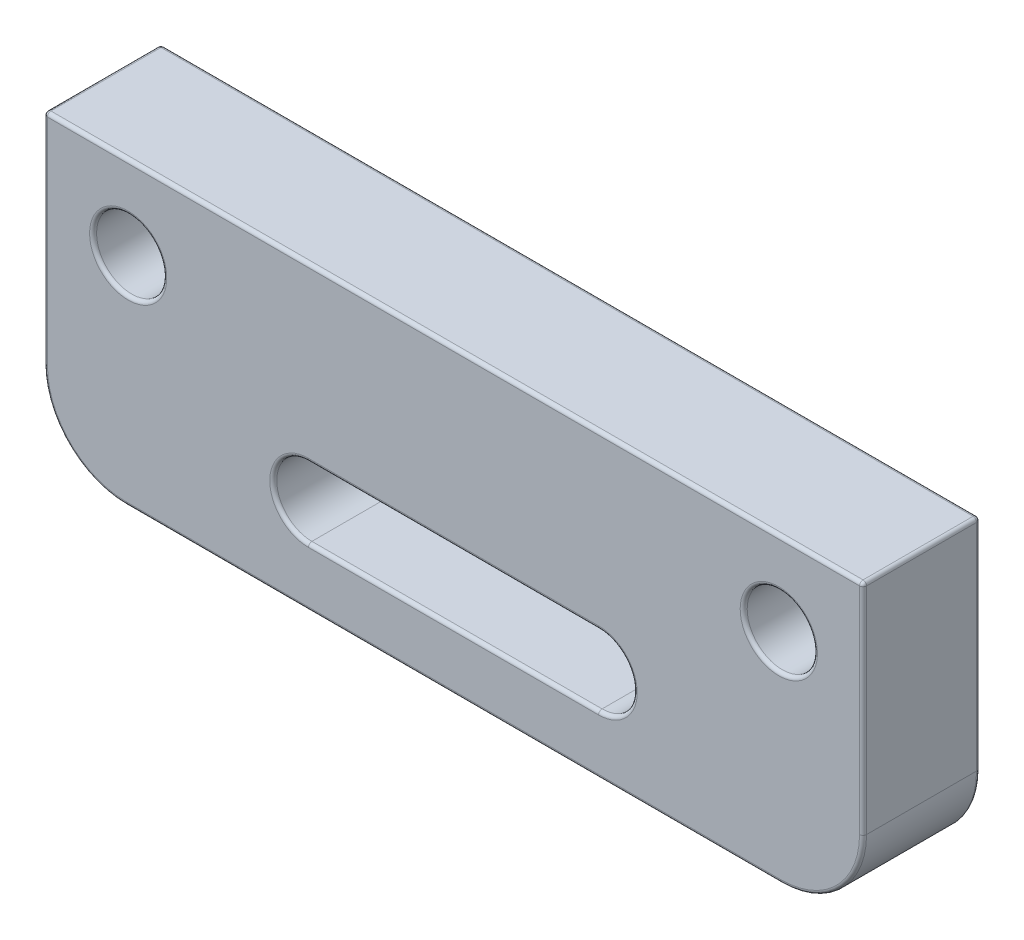
SolidWorks part; units mm, degrees
ref_plane "Front Plane" through (0, 0, 0) normal (0, 0, 1) x (1, 0, 0)
ref_plane "Top Plane" through (0, 0, 0) normal (0, 1, 0) x (1, 0, 0)
ref_plane "Right Plane" through (0, 0, 0) normal (1, 0, 0) x (0, 0, -1)
sketch "Sketch1" plane through (0, 0, 0) normal (0, 0, 1) x (1, 0, 0)
  line L0 (0, 25.7) -> (0, -19.3) construction
  line L1 (-11.3, -6.3) -> (11.3, -6.3)
  line L2 (-11.3, -6.3) -> (-11.3, 6.3)
  line L3 (-11.3, 6.3) -> (11.3, 6.3)
  line L4 (11.3, -6.3) -> (11.3, 6.3)
  line L5 (-11.3, -6.3) -> (11.3, 6.3) construction
  line L6 (-11.3, 6.3) -> (11.3, -6.3) construction
  line L7 (-6.2, -15.3) -> (6.2, -15.3) construction
  line L8 (-6.2, -13.8) -> (6.2, -13.8)
  line L9 (-6.2, -16.8) -> (6.2, -16.8)
  line L11 (-17.5, 8.7) -> (17.5, 8.7) construction
  line L12 (-17.5, 8.7) -> (-17.5, -19.3)
  line L13 (-17.5, -19.3) -> (17.5, -19.3)
  line L14 (17.5, 8.7) -> (17.5, -19.3)
  circle A0 centre (-13.9, 0) radius 1
  circle A1 centre (-13.9, -10) radius 1.5
  arc A2 (-6.2, -13.8) -> (-6.2, -16.8) centre (-6.2, -15.3) ccw
  arc A3 (6.2, -16.8) -> (6.2, -13.8) centre (6.2, -15.3) ccw
  circle A4 centre (-8.5, 16.3) radius 2
  circle A5 centre (8.5, 16.3) radius 2
  circle A6 centre (13.9, 0) radius 1
  circle A7 centre (13.9, -10) radius 1.5
  arc A8 (-17.5, 8.7) -> (17.5, 8.7) centre (0, 8.1926) cw
  point P0 (0, 0)
  point P14 (0, -15.3)
  point P25 (0, 25.7)
  point P33 (0, 0)
  point P34 (11.3, 0)
  dimension "D3" = 2
  dimension "D6" = 3
  dimension "D10" = 1.5
  dimension "D12" = 4
  dimension "D1" = 22.6
  dimension "D2" = 12.6
  dimension "D4" = 2.6
  dimension "D7" = 10
  dimension "D8" = 12.4
  dimension "D9" = 4
  dimension "D11" = 45
  dimension "D13" = 8.5
  dimension "D14" = 10
  dimension "D15" = 28
  dimension "D16" = 35
  dimension "D17" = 13
extrude "Boss-Extrude1" add sketch "Sketch1" along normal blind 5
fillet "Fillet1" radius 3.5 2 edges at (17.5, -19.3, 2.5) (-17.5, -19.3, 2.5)
fillet "Fillet2" radius 0.15 40 edges at (12.4, -10, 0) (6.5, 16.3, 0) (7.7, -15.3, 0) (0, -16.8, 0) (-7.7, -15.3, 0) (0, -13.8, 0) (-12.4, -10, 0) (-11.3, 0, 0) (0, 6.3, 0) (11.3, 0, 0) (0, -6.3, 0) (0, 25.7, 0) (-17.5, -3.55, 0) (-16.4749, -18.2749, 0) (0, -19.3, 0) (16.4749, -18.2749, 0) (17.5, -3.55, 0) (-12.9, 0, 0) (-6.5, 16.3, 0) (12.9, 0, 0) (12.4, -10, 5) (12.9, 0, 5) (6.5, 16.3, 5) (-6.5, 16.3, 5) (0, -16.8, 5) (7.7, -15.3, 5) (0, -13.8, 5) (-7.7, -15.3, 5) (-16.4749, -18.2749, 5) (-17.5, -3.55, 5) (0, 25.7, 5) (17.5, -3.55, 5) (16.4749, -18.2749, 5) (0, -19.3, 5) (0, 6.3, 5) (-11.3, 0, 5) (0, -6.3, 5) (11.3, 0, 5) (-12.9, 0, 5) (-12.4, -10, 5)
sketch "Sketch2" plane through (0, 0, 5) normal (0, 0, 1) x (1, 0, 0)
  line L0 (-22.35, -6.45) -> (27.65, -6.45)
  line L1 (11.45, -6.45) -> (-11.45, -6.45) construction
  line L2 (-17.35, 8.6978) -> (-17.35, -15.8) construction
  dimension "D1" = 50
  dimension "D2" = 5
extrude "Cut-Extrude1" cut sketch "Sketch2" against normal through all and the other way through all
fillet "Fillet3" radius 0.15 8 edges at (-17.5, -6.45, 2.5) (-17.4561, -6.45, 0.0439) (0, -6.45, 0) (17.4561, -6.45, 0.0439) (17.5, -6.45, 2.5) (17.4561, -6.45, 4.9561) (0, -6.45, 5) (-17.4561, -6.45, 4.9561)
